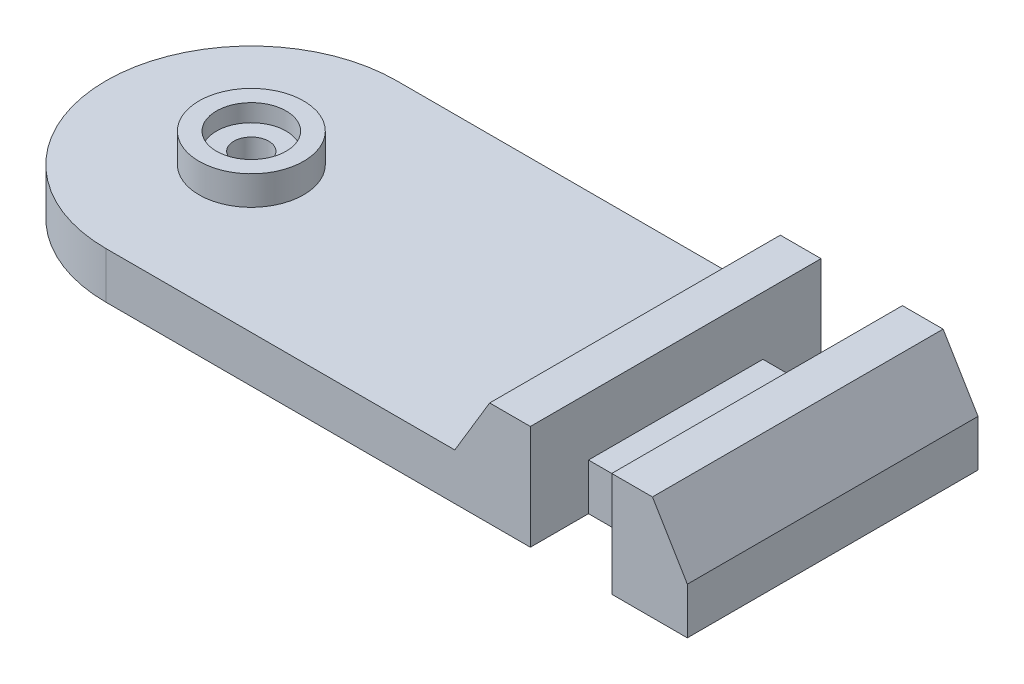
SolidWorks part; units mm, degrees
material "ABS"
ref_plane "前视基准面" through (0, 0, 0) normal (0, 0, 1) x (1, 0, 0)
ref_plane "上视基准面" through (0, 0, 0) normal (0, 1, 0) x (1, 0, 0)
ref_plane "右视基准面" through (0, 0, 0) normal (1, 0, 0) x (0, 0, -1)
sketch "草图1" plane through (0, 0, 0) normal (0, 1, 0) x (1, 0, 0)
  line L0 (0, 12.5) -> (50, 12.5)
  line L1 (50, 12.5) -> (50, -12.5)
  line L2 (50, -12.5) -> (0, -12.5)
  line L3 (-17.9664, 0) -> (77.456, 0) construction
  circle A0 centre (0, 0) radius 12.5
  circle A1 centre (0, 0) radius 1.5
  circle A2 centre (40, 0) radius 1.5
  dimension "D1" = 25
  dimension "D3" = 3
  dimension "D4" = 3
  dimension "D2" = 50
  dimension "D5" = 40
extrude "凸台-拉伸1" add sketch "草图1" along normal blind 4 contours A0 L3 A1 | L3 A0 A1 | A0 L3 A2 L1 L0 | L3 A0 L2 L1 A2
sketch "草图2" plane through (0, 4, 0) normal (0, 1, 0) x (1, 0, 0)
  circle A0 centre (0, 0) radius 3
  circle A1 centre (0, 0) radius 4.5
  dimension "D1" = 6
  dimension "D2" = 9
extrude "凸台-拉伸2" add sketch "草图2" along normal blind 2.5
sketch "草图3" plane through (0, 0, 12.5) normal (0, 0, 1) x (1, 0, 0)
  line L0 (40, 13.5103) -> (40, -9.5748) construction
  line L1 (33, 9) -> (47, 9)
  line L2 (47, 9) -> (50, 4)
  line L3 (50, 4) -> (30, 4)
  line L4 (50, 4) -> (0, 4) construction
  line L5 (33, 9) -> (30, 4)
  point P11 (40, 4)
  point P12 (40, 9)
  dimension "D1" = 40
  dimension "D2" = 7
  dimension "D3" = 5
extrude "凸台-拉伸3" add sketch "草图3" against normal up to surface (25 mm away) up to face at (25, 2, -12.5)
sketch "草图4" plane through (0, 0, 12.5) normal (0, 0, 1) x (1, 0, 0)
  line L0 (40, 14.712) -> (40, -12.897) construction
  line L1 (36.5, 9) -> (43.5, 9)
  line L2 (47, 9) -> (33, 9) construction
  line L3 (43.5, 9) -> (43.5, 4)
  line L4 (43.5, 4) -> (36.5, 4)
  line L5 (36.5, 9) -> (36.5, 4)
  point P10 (40, 4)
  point P11 (40, 9)
  dimension "D1" = 40
  dimension "D2" = 3.5
  dimension "D3" = 5
extrude "切除-拉伸1" cut sketch "草图4" against normal through all
sketch "草图5" plane through (0, 4, 0) normal (0, 1, 0) x (1, 0, 0)
  line L0 (-19.9448, 0) -> (64.5272, 0) construction
  line L1 (36.5, -12.5) -> (43.5, -12.5)
  line L2 (43.5, -12.5) -> (43.5, -7.5)
  line L3 (43.5, 12.5) -> (43.5, -12.5) construction
  line L4 (43.5, -7.5) -> (36.5, -7.5)
  line L5 (36.5, 12.5) -> (36.5, -12.5) construction
  line L6 (36.5, -7.5) -> (36.5, -12.5)
  line L7 (36.5, 7.5) -> (36.5, 12.5)
  line L8 (36.5, 12.5) -> (43.5, 12.5)
  line L9 (43.5, 12.5) -> (43.5, 7.5)
  line L10 (43.5, 7.5) -> (36.5, 7.5)
  dimension "D1" = 5
extrude "切除-拉伸2" cut sketch "草图5" against normal through all
sketch "草图6" plane through (0, 4, 0) normal (0, 1, 0) x (1, 0, 0)
  circle A0 centre (0, 0) radius 3
  circle A1 centre (0, 0) radius 1.5
extrude "凸台-拉伸4" add sketch "草图6" along normal blind 1
